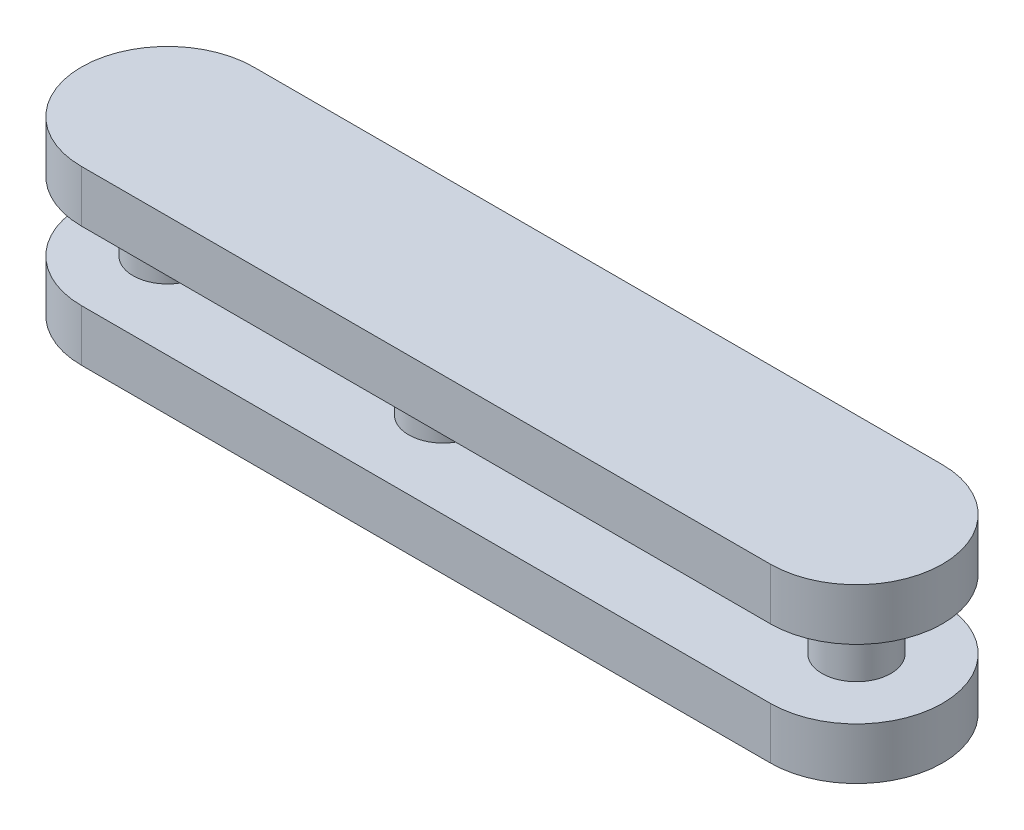
SolidWorks part; units mm, degrees
ref_plane "Plan de face" through (0, 0, 0) normal (0, 0, 1) x (1, 0, 0)
ref_plane "Plan de dessus" through (0, 0, 0) normal (0, 1, 0) x (1, 0, 0)
ref_plane "Plan de droite" through (0, 0, 0) normal (1, 0, 0) x (0, 0, -1)
sketch "Esquisse1" plane through (0, 0, 0) normal (0, 1, 0) x (1, 0, 0)
  line L1 (0, 0) -> (50, 0)
  line L2 (0, 0) -> (0, 10)
  line L3 (0, 10) -> (50, 10)
  line L4 (50, 0) -> (50, 10)
  dimension "D1" = 50
  dimension "D2" = 10
extrude "Boss.-Extru.1" add sketch "Esquisse1" along normal blind 10
sketch "Esquisse2" plane through (0, 0, 0) normal (0, 0, 1) x (1, 0, 0)
  line L0 (0, 10) -> (0, 0) construction
  line L1 (0, 3) -> (20, 3)
  line L2 (0, 3) -> (0, 7)
  line L3 (0, 7) -> (20, 7)
  line L5 (50, 10) -> (50, 0) construction
  line L6 (50, 3) -> (30, 3)
  line L7 (50, 3) -> (50, 7)
  line L8 (50, 7) -> (30, 7)
  line L10 (0, 0) -> (50, 0) construction
  line L12 (20, 7) -> (30, 7)
  line L13 (20, 3) -> (30, 3)
  dimension "D1" = 4
  dimension "D2" = 4
  dimension "D3" = 20
  dimension "D4" = 20
  dimension "D5" = 3
  dimension "D6" = 3
extrude "Enlèv. mat.-Extru.1" cut sketch "Esquisse2" against normal blind 10
sketch "Esquisse3" plane through (0, 3, 0) normal (0, 1, 0) x (1, 0, 0)
  line L0 (0, 10) -> (0, 0) construction
  line L1 (0, 0) -> (50, 0) construction
  line L2 (50, 10) -> (50, 0) construction
  line L3 (0, 0) -> (50, 0) construction
  circle A0 centre (5, 5) radius 2
  circle A1 centre (45, 5) radius 2
  dimension "D1" = 4
  dimension "D4" = 4
  dimension "D2" = 5
  dimension "D3" = 5
  dimension "D5" = 5
  dimension "D6" = 5
extrude "Boss.-Extru.2" add sketch "Esquisse3" along normal blind 5
sketch "Esquisse4" plane through (0, 10, 0) normal (0, 1, 0) x (1, 0, 0)
  line L0 (50, 10) -> (0, 10) construction
  line L1 (0, 0) -> (50, 0) construction
  line L2 (0, 10) -> (0, 0) construction
  line L3 (50, 0) -> (50, 10) construction
  line L4 (5, 0) -> (-6.3043, 0)
  line L5 (-6.3043, 0) -> (-6.3043, 10)
  line L6 (-6.3043, 10) -> (5, 10)
  line L7 (45, 0) -> (61.2807, 0)
  line L8 (61.2807, 0) -> (61.2807, 10)
  line L9 (61.2807, 10) -> (45, 10)
  arc A0 (5, 10) -> (5, 0) centre (5, 5) ccw
  arc A1 (45, 10) -> (45, 0) centre (45, 5) cw
  dimension "D1" = 5
  dimension "D2" = 5
  dimension "D3" = 5
  dimension "D4" = 5
  dimension "D5" = 5
  dimension "D6" = 5
extrude "Enlèv. mat.-Extru.2" cut sketch "Esquisse4" against normal through all
sketch "Esquisse6" plane through (0, 7, 0) normal (0, -1, 0) x (1, 0, 0)
  line L0 (45, 0) -> (5, 0) construction
  circle A0 centre (21, -5) radius 2
  circle A1 centre (45, -5) radius 2 construction
  dimension "D1" = 4
  dimension "D2" = 24
  dimension "D3" = 5
extrude "Boss.-Extru.3" add sketch "Esquisse6" along normal blind 5
